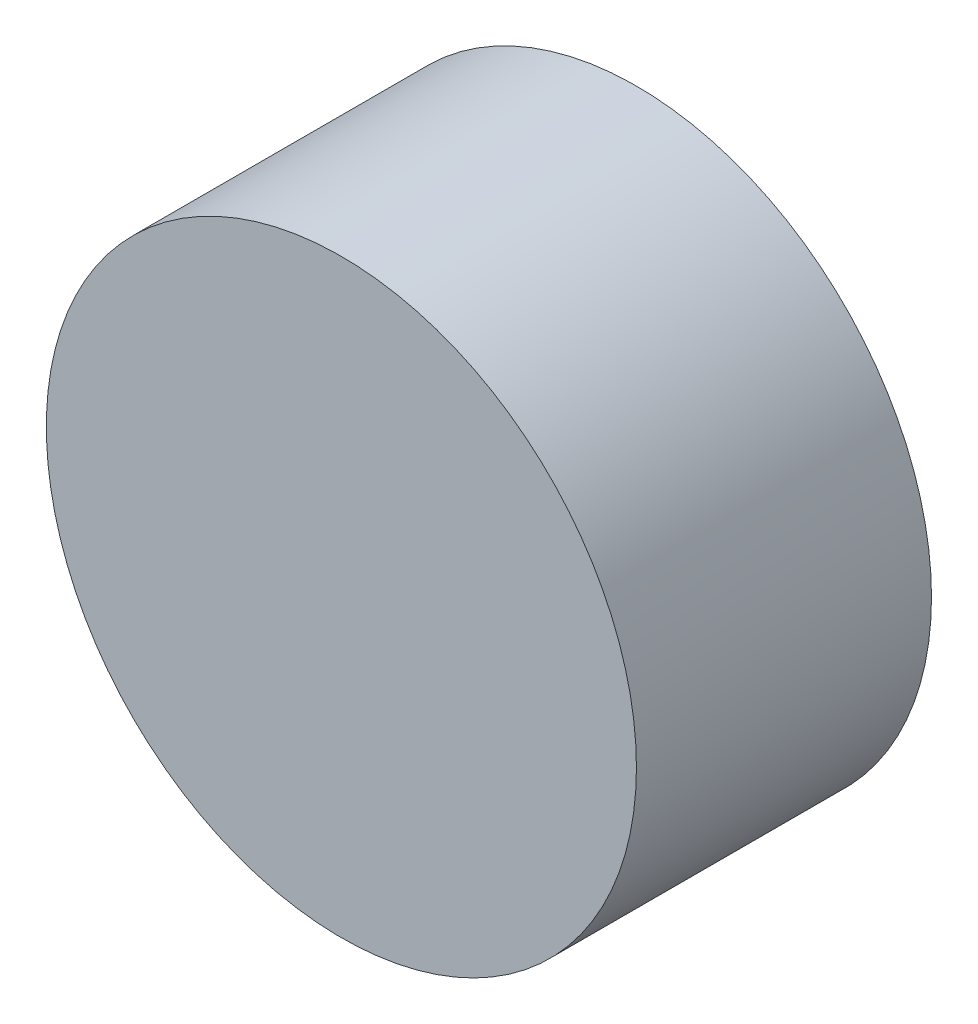
SolidWorks part; units mm, degrees
ref_plane "前视基准面" through (0, 0, 0) normal (0, 0, 1) x (1, 0, 0)
ref_plane "上视基准面" through (0, 0, 0) normal (0, 1, 0) x (1, 0, 0)
ref_plane "右视基准面" through (0, 0, 0) normal (1, 0, 0) x (0, 0, -1)
sketch "草图1" plane through (0, 0, 0) normal (0, 0, 1) x (1, 0, 0)
  circle A0 centre (0, 0) radius 10
  dimension "D1" = 20
extrude "凸台-拉伸1" add sketch "草图1" along normal blind 10
